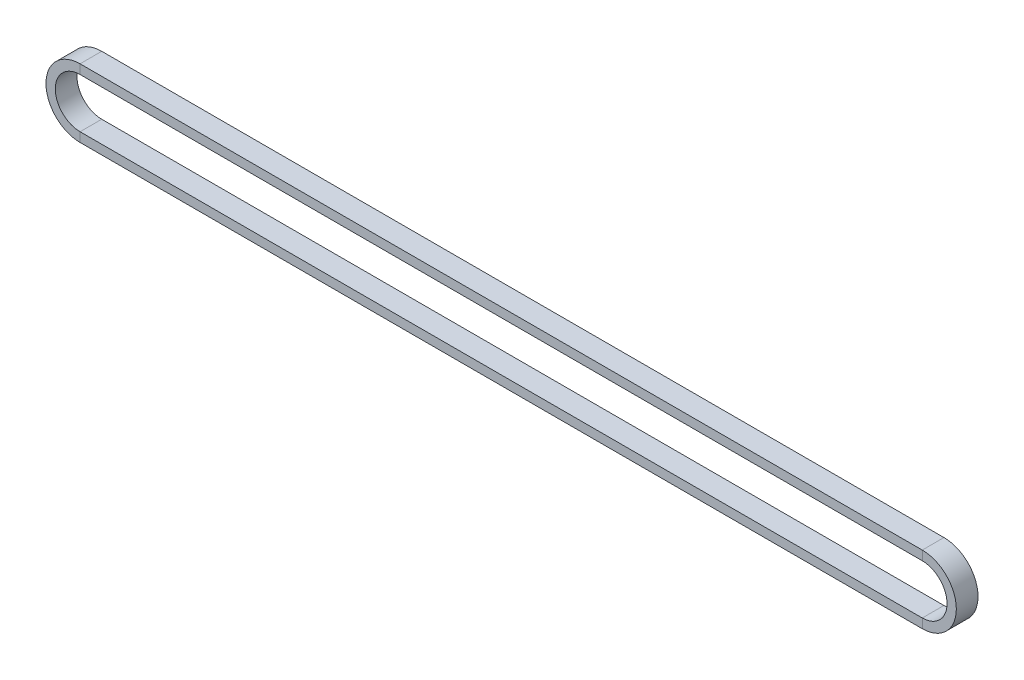
SolidWorks part; units mm, degrees
material "EPDM 60 Durometer"
ref_plane "Ebene vorne" through (0, 0, 0) normal (0, 0, 1) x (1, 0, 0)
ref_plane "Ebene oben" through (0, 0, 0) normal (0, 1, 0) x (1, 0, 0)
ref_plane "Ebene rechts" through (0, 0, 0) normal (1, 0, 0) x (0, 0, -1)
sketch "Skizze2" plane through (0, 0, 0) normal (0, 0, 1) x (1, 0, 0)
  line L0 (0, 0) -> (1, 0) construction
  line L1 (0, 0) -> (0, 1) construction
  line L2 (0, -40) -> (-1360, -40)
  line L3 (-1360, 40) -> (0, 40)
  arc A0 (0, 40) -> (0, -40) centre (0, 0) cw
  arc A1 (-1360, -40) -> (-1360, 40) centre (-1360, 0) cw
sketch3d "3D-Skizze1"
  line L0 (-1360, 40, 0) -> (0, 40, 0) construction
  line L2 (0, 55, -17.5) -> (0, 55, 17.5)
  line L3 (0, 55, -17.5) -> (0, 40, -17.5)
  line L4 (0, 40, -17.5) -> (0, 40, 17.5)
  line L5 (0, 55, 17.5) -> (0, 40, 17.5)
  point P7 (0, 40, 0)
  dimension "D1" = 15
  dimension "D2" = 35
sweep "Austragung1" add profiles "3D-Skizze1" path "Skizze2"
